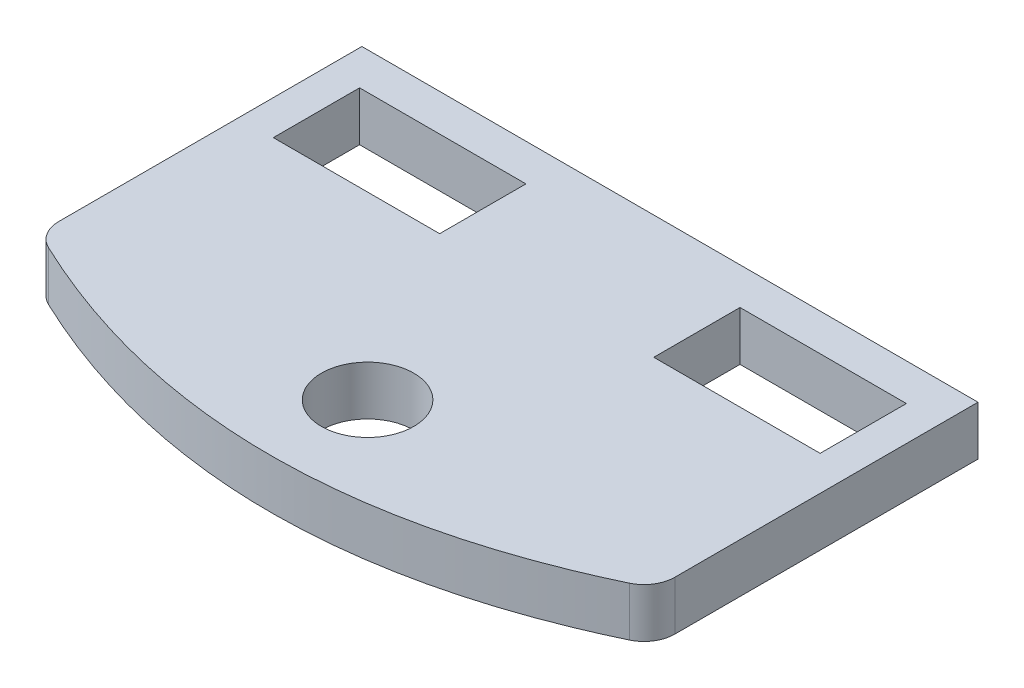
SolidWorks part; units mm, degrees
ref_plane "정면" through (0, 0, 0) normal (0, 0, 1) x (1, 0, 0)
ref_plane "윗면" through (0, 0, 0) normal (0, 1, 0) x (1, 0, 0)
ref_plane "우측면" through (0, 0, 0) normal (1, 0, 0) x (0, 0, -1)
sketch "스케치1" plane through (0, 0, 0) normal (0, 1, 0) x (1, 0, 0)
  line L0 (0, -55) -> (0, 55) construction
  line L1 (-10, 5.6345) -> (10, 5.6345)
  line L2 (-10, 5.6345) -> (-10, -4.2055)
  line L4 (10, 5.6345) -> (10, -4.2072)
  line L5 (-10, 5.6345) -> (9.3504, -5.2685) construction
  line L6 (-9.3504, -5.2685) -> (10, 5.6345) construction
  line L7 (8.875, 1.6345) -> (8.875, 4.4345)
  line L8 (-8.875, 1.6345) -> (-3.475, 1.6345)
  line L9 (-8.875, 1.6345) -> (-8.875, 4.4345)
  line L10 (-8.875, 4.4345) -> (-3.475, 4.4345)
  line L11 (-3.475, 1.6345) -> (-3.475, 4.4345)
  line L12 (-8.875, 1.6345) -> (-3.475, 4.4345) construction
  line L13 (-8.875, 4.4345) -> (-3.475, 1.6345) construction
  line L14 (8.875, 1.6345) -> (3.475, 4.4345) construction
  line L15 (8.875, 4.4345) -> (3.475, 1.6345) construction
  line L16 (8.875, 1.6345) -> (3.475, 1.6345)
  line L17 (3.475, 1.6345) -> (3.475, 4.4345)
  line L18 (8.875, 4.4345) -> (3.475, 4.4345)
  line L19 (0.025, -4.2055) -> (-12.1362, -4.2055) construction
  circle A0 centre (0.025, -4.2055) radius 1.5
  arc A1 (-10, -4.2055) -> (-9.4282, -5.1092) centre (-9, -4.2055) ccw
  arc A2 (9.4303, -5.1099) -> (10, -4.2072) centre (9, -4.2072) ccw
  spline S0 degree 3 poles (-9.4282, -5.1092) (-6.286, -6.598) (-0.009, -8.0873) (6.3065, -6.5988) (9.4303, -5.1099) knots 0.02859 0.02859 0.02859 0.02859 0.499915 0.971328 0.971328 0.971328 0.971328
  point P0 (0, 0)
  point P7 (-6.175, 3.0345)
  point P18 (6.175, 3.0345)
  point P26 (0, 0)
  point P29 (0, 0)
  dimension "D7" = 3
  dimension "D2" = 0
  dimension "D8" = 1
  dimension "D9" = 5.84
  dimension "D1" = 20
  dimension "D3" = 5.4
  dimension "D4" = 2.8
  dimension "D5" = 6.95
  dimension "D6" = 1.2
extrude "보스-돌출1" add sketch "스케치1" along normal blind 1.6
